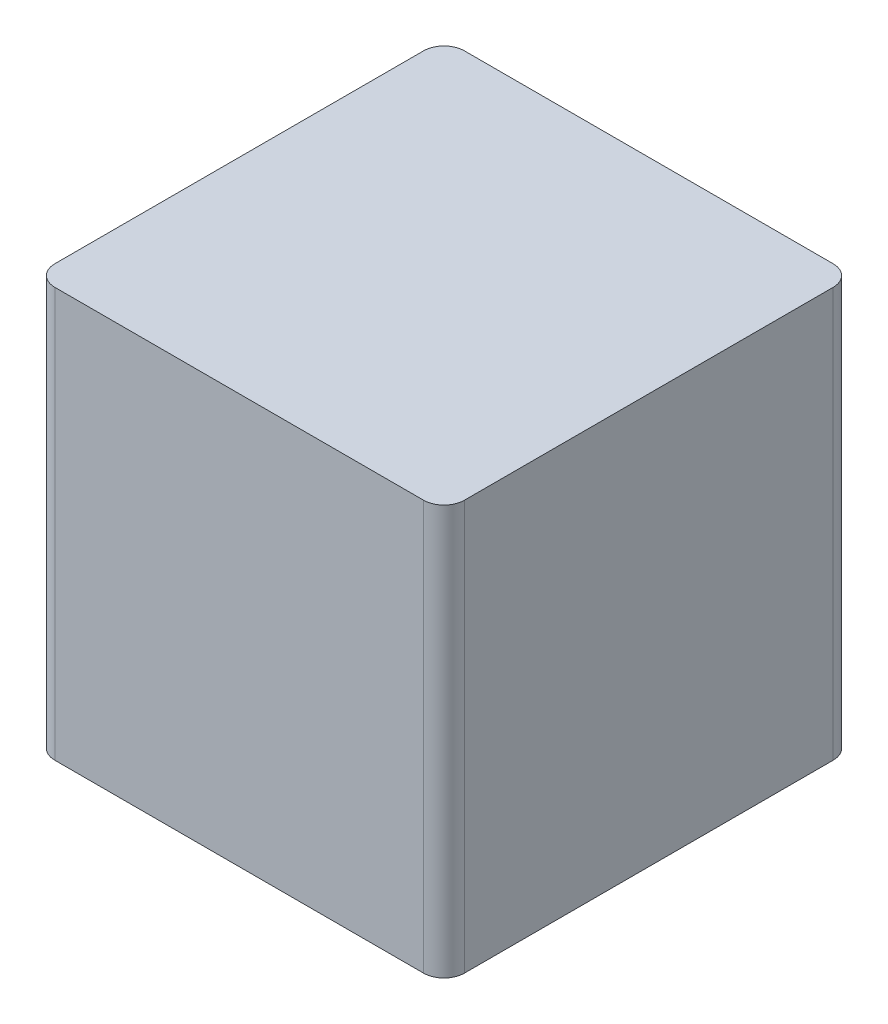
SolidWorks part; units mm, degrees
material "PVC 0.007 Plasticized"
ref_plane "Front Plane" through (0, 0, 0) normal (0, 0, 1) x (1, 0, 0)
ref_plane "Top Plane" through (0, 0, 0) normal (0, 1, 0) x (1, 0, 0)
ref_plane "Right Plane" through (0, 0, 0) normal (1, 0, 0) x (0, 0, -1)
sketch "Sketch1" plane through (0, 0, 0) normal (0, 1, 0) x (1, 0, 0)
  line L1 (-10, -10) -> (10, -10)
  line L2 (-10, -10) -> (-10, 10)
  line L3 (-10, 10) -> (10, 10)
  line L4 (10, -10) -> (10, 10)
  line L5 (-10, -10) -> (10, 10) construction
  line L6 (-10, 10) -> (10, -10) construction
  point P0 (0, 0)
  dimension "D1" = 20
  dimension "D2" = 20
extrude "Boss-Extrude1" add sketch "Sketch1" along normal blind 20
fillet "Fillet1" radius 1 4 edges at (-10, 10, -10) (10, 10, -10) (10, 10, 10) (-10, 10, 10)
